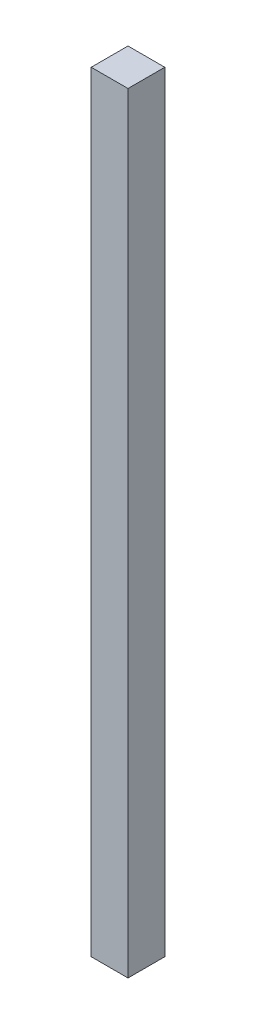
SolidWorks part; units mm, degrees
ref_plane "Front Plane" through (0, 0, 0) normal (0, 0, 1) x (1, 0, 0)
ref_plane "Top Plane" through (0, 0, 0) normal (0, 1, 0) x (1, 0, 0)
ref_plane "Right Plane" through (0, 0, 0) normal (1, 0, 0) x (0, 0, -1)
sketch "Sketch1" plane through (0, 0, 0) normal (0, 1, 0) x (1, 0, 0)
  line L1 (-44.45, -44.45) -> (44.45, -44.45)
  line L2 (-44.45, -44.45) -> (-44.45, 44.45)
  line L3 (-44.45, 44.45) -> (44.45, 44.45)
  line L4 (44.45, -44.45) -> (44.45, 44.45)
  line L5 (-44.45, -44.45) -> (44.45, 44.45) construction
  line L6 (-44.45, 44.45) -> (44.45, -44.45) construction
  point P0 (0, 0)
  dimension "D1" = 88.9
  dimension "D2" = 88.9
extrude "Boss-Extrude1" add sketch "Sketch1" along normal mid plane 1861.3437
